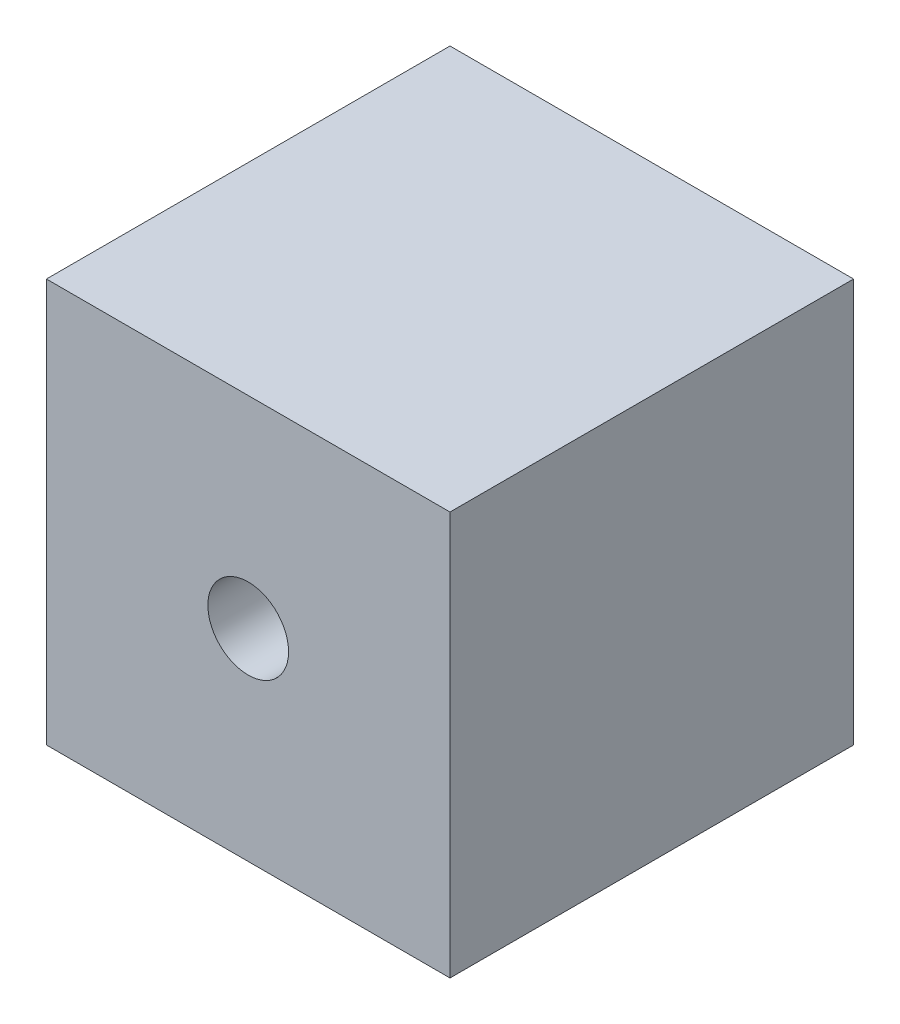
SolidWorks part; units mm, degrees
ref_plane "Front" through (0, 0, 0) normal (0, 0, 1) x (1, 0, 0)
ref_plane "Top" through (0, 0, 0) normal (0, 1, 0) x (1, 0, 0)
ref_plane "Right" through (0, 0, 0) normal (1, 0, 0) x (0, 0, -1)
sketch "Esquisse1" plane through (0, 0, 0) normal (0, 1, 0) x (1, 0, 0)
  line L1 (0, 0) -> (60, 0)
  line L2 (0, 0) -> (0, 60)
  line L3 (0, 60) -> (60, 60)
  line L4 (60, 0) -> (60, 60)
  dimension "D1" = 60
  dimension "D2" = 60
extrude "Boss.-Extru.1" add sketch "Esquisse1" along normal blind 60
sketch "Esquisse2" plane through (0, 0, 0) normal (0, 0, 1) x (1, 0, 0)
  line L1 (0, 0) -> (60, 0) construction
  circle A0 centre (30, 30) radius 6
  dimension "D3" = 12
  dimension "D1" = 30
  dimension "D2" = 30
extrude "Enlèv. mat.-Extru.1" cut sketch "Esquisse2" against normal blind 20
sketch "Esquisse3" plane through (0, 0, 0) normal (-1, 0, 0) x (0, 0, 1)
  circle A0 centre (-30, 30) radius 6
  dimension "D1" = 12
  dimension "D2" = 30
  dimension "D3" = 30
extrude "Enlèv. mat.-Extru.2" cut sketch "Esquisse3" against normal blind 20
